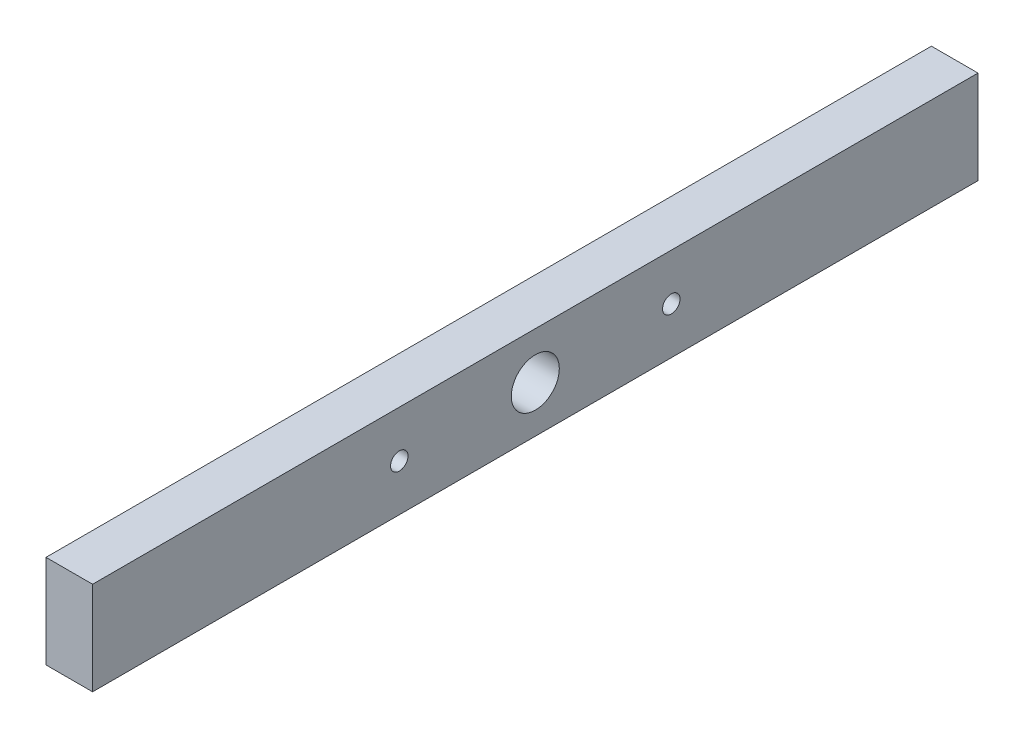
SolidWorks part; units mm, degrees
ref_plane "Front Plane" through (0, 0, 0) normal (0, 0, 1) x (1, 0, 0)
ref_plane "Top Plane" through (0, 0, 0) normal (0, 1, 0) x (1, 0, 0)
ref_plane "Right Plane" through (0, 0, 0) normal (1, 0, 0) x (0, 0, -1)
sketch "Sketch2" plane through (0, 0, 0) normal (1, 0, 0) x (0, 0, -1)
  line L1 (0, 0) -> (380, 0)
  line L2 (0, 0) -> (0, 40)
  line L3 (0, 40) -> (380, 40)
  line L4 (380, 0) -> (380, 40)
  line L5 (190, 0) -> (275.0005, 0)
  circle A2 centre (190, 20) radius 10.3017
  circle A3 centre (131.63, 20) radius 3.75
  circle A4 centre (248.37, 20) radius 3.75
extrude "Boss-Extrude2" add sketch "Sketch2" along normal blind 20
sketch "Sketch3" plane through (0, 0, 0) normal (-1, 0, 0) x (0, 0, 1)
  line L0 (-190, 20) -> (-131.635, 20)
  line L1 (-190, 20) -> (-248.365, 20)
  dimension "D1" = 58.365
  dimension "D2" = 58.365
